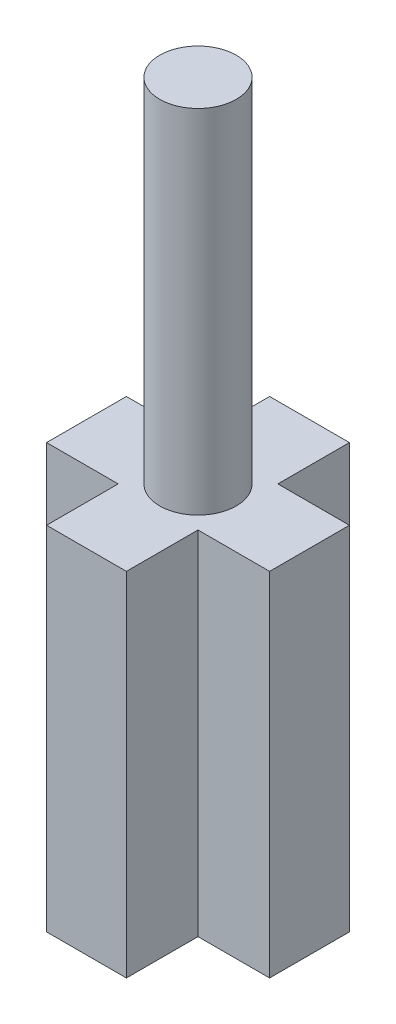
SolidWorks part; units mm, degrees
ref_plane "Front Plane" through (0, 0, 0) normal (0, 0, 1) x (1, 0, 0)
ref_plane "Top Plane" through (0, 0, 0) normal (0, 1, 0) x (1, 0, 0)
ref_plane "Right Plane" through (0, 0, 0) normal (1, 0, 0) x (0, 0, -1)
sketch "Sketch1" plane through (0, 0, 0) normal (0, 1, 0) x (1, 0, 0)
  line L0 (0.8636, 0.8636) -> (2.413, 0.8636)
  line L1 (-0.8636, 2.413) -> (0.8636, 2.413)
  line L2 (-0.8636, 2.413) -> (-0.8636, 0.8636)
  line L3 (-0.8636, -2.413) -> (0.8636, -2.413)
  line L4 (0.8636, 2.413) -> (0.8636, 0.8636)
  line L5 (-2.413, 0.8636) -> (0, 0) construction
  line L6 (2.413, -0.8636) -> (0, 0) construction
  line L7 (-2.413, -0.8636) -> (-0.8636, -0.8636)
  line L8 (-2.413, -0.8636) -> (-2.413, 0.8636)
  line L9 (-2.413, 0.8636) -> (-0.8636, 0.8636)
  line L10 (2.413, -0.8636) -> (2.413, 0.8636)
  line L11 (0, 0) -> (2.413, 0.8636) construction
  line L12 (-2.413, -0.8636) -> (0, 0) construction
  line L13 (0.8636, 2.413) -> (0, 0) construction
  line L14 (-0.8636, -0.8636) -> (-0.8636, -2.413)
  line L15 (0, 0) -> (-0.8636, 2.413) construction
  line L16 (-0.8636, -2.413) -> (0, 0) construction
  line L17 (0.8636, -0.8636) -> (0.8636, -2.413)
  line L19 (0.8636, -0.8636) -> (2.413, -0.8636)
  line L21 (0, 0) -> (0.8636, -2.413) construction
  point P0 (0, 0)
  point P6 (0, 0)
  dimension "D1" = 1.7272
extrude "Boss-Extrude1" add sketch "Sketch1" along normal blind 7.62
sketch "Sketch2" plane through (0, 7.62, 0) normal (0, 1, 0) x (1, 0, 0)
  circle A2 centre (0, 0) radius 0.828
  dimension "D1" = 1.6561
extrude "Boss-Extrude2" add sketch "Sketch2" along normal blind 7.62 contours A2
